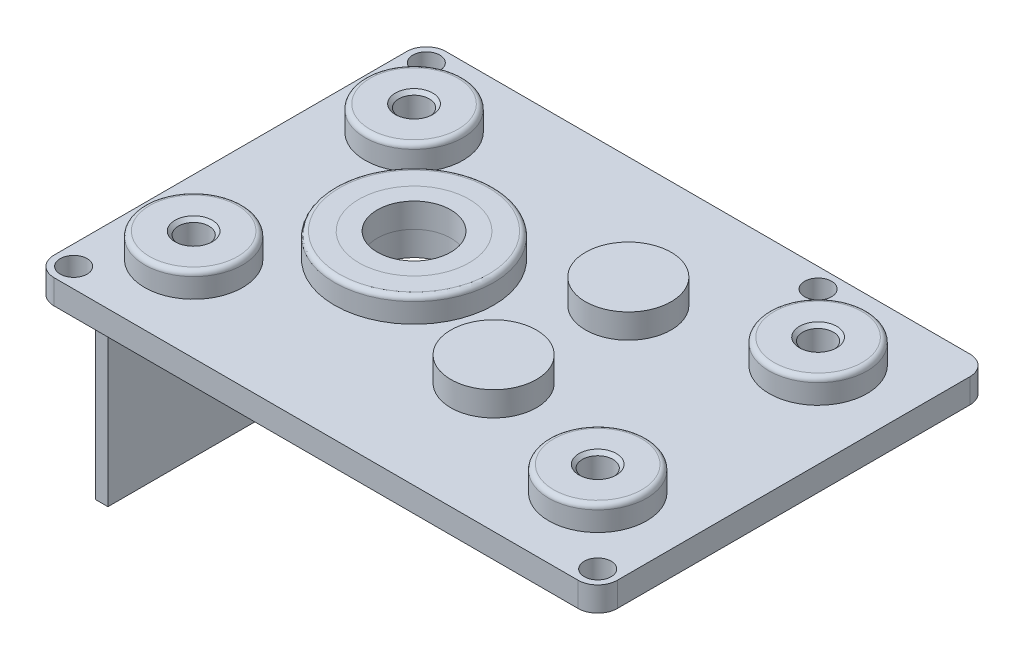
SolidWorks part; units mm, degrees
material "201.0-T7 Insulated Mold Casting (SS)"
ref_plane "Front Plane" through (0, 0, 0) normal (0, 0, 1) x (1, 0, 0)
ref_plane "Top Plane" through (0, 0, 0) normal (0, 1, 0) x (1, 0, 0)
ref_plane "Right Plane" through (0, 0, 0) normal (1, 0, 0) x (0, 0, -1)
sketch "Sketch2" plane through (0, 0, 0) normal (0, 1, 0) x (1, 0, 0)
  line L0 (0, 0) -> (-15, 0) construction
  line L1 (-15, 16) -> (31, 16)
  line L2 (-15, 16) -> (-15, -16)
  line L3 (-15, -16) -> (31, -16)
  line L4 (31, 16) -> (31, -16)
  dimension "D1" = 32
  dimension "D2" = 46
  dimension "D3" = 15
extrude "Boss-Extrude2" add sketch "Sketch2" along normal blind 2
sketch "Sketch6" plane through (0, 2, 0) normal (0, 1, 0) x (1, 0, 0)
  circle A0 centre (0, 0) radius 3
  dimension "D1" = 6
extrude "Cut-Extrude1" cut sketch "Sketch6" against normal through all
sketch "Sketch7" plane through (0, 2, 0) normal (0, 1, 0) x (1, 0, 0)
  circle A0 centre (0, 0) radius 4.5
  circle A1 centre (0, 0) radius 3
  circle A2 centre (0, 0) radius 3 construction
  dimension "D1" = 9
extrude "Boss-Extrude4" add sketch "Sketch7" along normal blind 2 separate body
sketch "Sketch8" plane through (0, 2, 0) normal (0, 1, 0) x (1, 0, 0)
  circle A0 centre (0, 0) radius 4.5
  circle A1 centre (0, 0) radius 4.5 construction
  circle A2 centre (0, 0) radius 6.5
  dimension "D1" = 13
extrude "Boss-Extrude5" add sketch "Sketch8" along normal blind 2 separate body
sketch "Sketch3" plane through (0, 2, 0) normal (0, 1, 0) x (1, 0, 0)
  line L0 (-15, 0) -> (31, 0) construction
  line L1 (-15, 16) -> (-15, -16) construction
  line L2 (31, -16) -> (31, 16) construction
  line L3 (8, -16) -> (8, 16) construction
  line L4 (-15, -16) -> (31, -16) construction
  line L5 (31, 16) -> (-15, 16) construction
  circle A0 centre (-9, 9) radius 4
  circle A1 centre (0, 0) radius 3 construction
  dimension "D1" = 8
  dimension "D2" = 9
  dimension "D3" = 9
extrude "Boss-Extrude3" add sketch "Sketch3" along normal blind 2
fillet "Fillet3" radius 0.4 1 edges at (0, 4, 6.5)
ref_plane "MP HORZ HOLES" through (8, 0, 0) normal (-1, 0, 0) x (0, 0, 1)
hole_wizard "M3x0.5 Tapped Hole1" positions "Sketch5" profile "Sketch4" tap size "M3x0.5" standard "ANSI Metric" end condition through all
sketch "Sketch5" plane through (0, 4, 0) normal (0, 1, 0) x (1, 0, 0)
  point P0 (-9, 9)
sketch "Sketch4" plane through (-9, 4, -9) normal (1, 0, 0) x (0, 0, 1)
  line L0 (0, 0) -> (0, 4)
  line L1 (0, 4) -> (1.25, 4)
  line L2 (1.25, 4) -> (1.25, 0.275)
  line L3 (1.25, 0.275) -> (1.525, 0)
  line L5 (1.525, 0) -> (0, 0)
  line L6 (-1.25, 0.275) -> (-1.525, 0) construction
  line L11 (0, -6.35) -> (0, 107.95) construction
  point P2 (0, 0)
  dimension "Thread Major Dia." = 2.5
  dimension "Thru Tap Drill Depth" = 4
  dimension "Near C'Sink Dia." = 3.05
  dimension "Near C'Sink Angle" = 90
pattern_linear "LPattern1" count 2 spacing 33 along (1, 0, 0) of "M3x0.5 Tapped Hole1", "Boss-Extrude3"
sketch "Sketch9" plane through (0, 2, 0) normal (0, 1, 0) x (1, 0, 0)
  line L0 (0, 0) -> (12, 0) construction
  line L1 (12, 0) -> (12, 5.5) construction
  circle A0 centre (12, 5.5) radius 3.5
  dimension "D1" = 7
  dimension "D2" = 12
  dimension "D3" = 5.5
extrude "Boss-Extrude6" add sketch "Sketch9" along normal blind 2
mirror "Mirror2" about plane through (0, 0, 0) normal (0, 0, 1) of "LPattern1", "Boss-Extrude3", "M3x0.5 Tapped Hole1"
mirror "Mirror3" about plane through (0, 0, 0) normal (0, 0, 1) of "Boss-Extrude6"
hole_wizard "M2 Clearance Hole1" positions "Sketch11" profile "Sketch10" hole size "M2" standard "ANSI Metric" end condition through all
sketch "Sketch11" plane through (0, 2, 0) normal (0, 1, 0) x (1, 0, 0)
  line L0 (-13.4, 14.4) -> (18.6, 14.4) construction
  line L2 (31, 16) -> (-15, 16) construction
  line L3 (-15, 16) -> (-15, -16) construction
  line L5 (-15, -16) -> (31, -16) construction
  line L6 (29.4, -14.4) -> (-13.4, -14.4) construction
  line L7 (-13.4, 14.4) -> (-13.4, -14.4) construction
  line L9 (31, -16) -> (31, 16) construction
  point P0 (-13.4, 14.4)
  point P4 (18.6, 14.4)
  point P6 (29.4, -14.4)
  point P23 (-13.4, -14.4)
  dimension "D1" = 1.6
  dimension "D2" = 1.6
  dimension "D3" = 1.6
  dimension "D4" = 1.6
  dimension "D5" = 32
sketch "Sketch10" plane through (-13.4, 2, -14.4) normal (1, 0, 0) x (0, 0, 1)
  line L0 (0, 0) -> (0, 2)
  line L1 (0, 2) -> (1.1, 2)
  line L2 (1.1, 2) -> (1.1, 0)
  line L5 (1.1, 0) -> (0, 0)
  line L11 (0, -6.35) -> (0, 107.95) construction
  dimension "Thru Hole Dia." = 2.2
  dimension "Thru Hole Depth" = 2
fillet "Fillet1" radius 1.6 4 edges at (31, 1, -16) (31, 1, 16) (-15, 1, -16) (-15, 1, 16)
sketch "Sketch12" plane through (0, 0, 0) normal (0, -1, 0) x (1, 0, 0)
  line L0 (-15, -14.4) -> (-15, 14.4) construction
  line L1 (-14, -11) -> (-15, -11)
  line L2 (-14, -11) -> (-14, 11)
  line L3 (-14, 11) -> (-15, 11)
  line L4 (-15, -11) -> (-15, 11)
  line L5 (-14, -11) -> (-15, 11) construction
  line L6 (-14, 11) -> (-15, -11) construction
  line L7 (0, 0) -> (-14.5, 0) construction
  point P0 (-14.5, 0)
  dimension "D1" = 1
  dimension "D2" = 22
extrude "Boss-Extrude7" add sketch "Sketch12" along normal blind 17
fillet "Fillet5" radius 0.4 4 edges at (24, 4, 5) (-9, 4, 5) (24, 4, -5) (-9, 4, -5)
